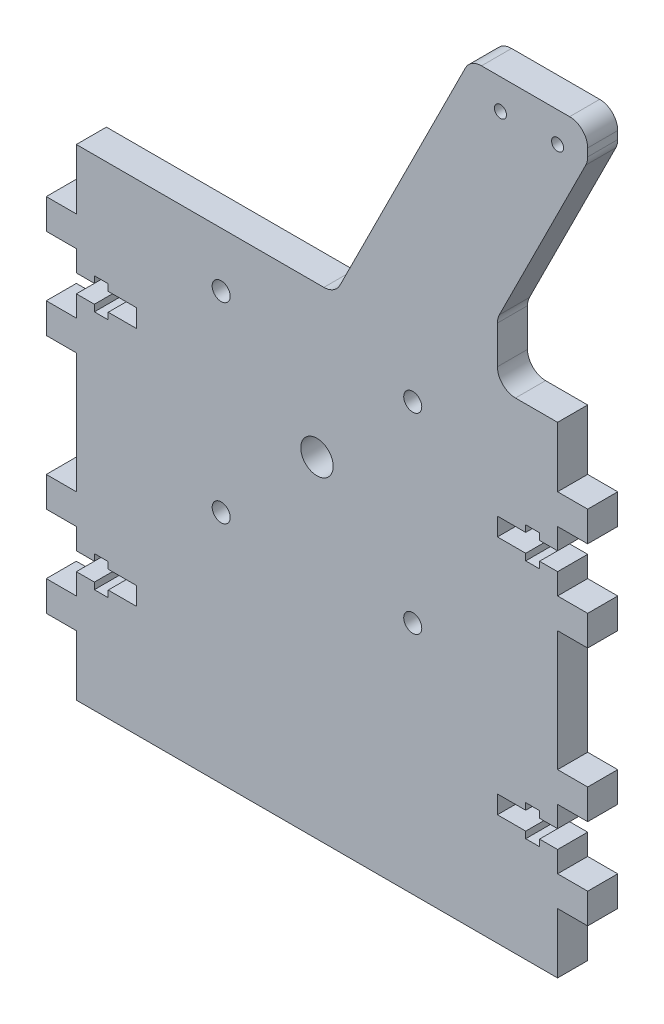
SolidWorks part; units mm, degrees
ref_plane "Front Plane" through (0, 0, 0) normal (0, 0, 1) x (1, 0, 0)
ref_plane "Top Plane" through (0, 0, 0) normal (0, 1, 0) x (1, 0, 0)
ref_plane "Right Plane" through (0, 0, 0) normal (1, 0, 0) x (0, 0, -1)
sketch "Sketch1" plane through (0, 0, 0) normal (0, 0, 1) x (1, 0, 0)
  line L0 (0, 0) -> (0, 80) construction
  line L1 (0, 80) -> (-80, 80)
  line L3 (-80, 0) -> (0, 0)
  line L4 (-40, 80) -> (-40, 0) construction
  line L5 (0, 40) -> (-80, 40) construction
  line L6 (0, 60) -> (-11.2208, 60) construction
  line L7 (0, 58.5) -> (0, 55)
  line L8 (5, 55) -> (5, 50)
  line L9 (5, 50) -> (0, 50)
  line L10 (5, 55) -> (0, 55)
  line L11 (0, 61.5) -> (0, 65)
  line L12 (0, 65) -> (5, 65)
  line L13 (5, 65) -> (5, 70)
  line L14 (5, 70) -> (0, 70)
  line L15 (0, 58.5) -> (0, 61.5) construction
  line L16 (0, 61.5) -> (-3, 61.5)
  line L17 (-5.3, 61.5) -> (-5.3, 62.6)
  line L18 (-3, 57.4) -> (-5.3, 57.4)
  line L19 (-3, 62.6) -> (-3, 61.5)
  line L20 (-5.3, 61.5) -> (-10, 61.5)
  line L21 (-10, 61.5) -> (-10, 58.5)
  line L22 (-10, 58.5) -> (-5.3, 58.5)
  line L23 (-3, 58.5) -> (-3, 57.4)
  line L24 (-5.3, 62.6) -> (-3, 62.6)
  line L25 (-5.3, 57.4) -> (-5.3, 58.5)
  line L26 (-3, 58.5) -> (0, 58.5)
  line L27 (-10, 60) -> (0, 60) construction
  line L28 (5, 10) -> (0, 10)
  line L29 (5, 15) -> (5, 10)
  line L30 (0, 15) -> (5, 15)
  line L31 (0, 18.5) -> (0, 15)
  line L32 (0, 18.5) -> (-3, 18.5)
  line L33 (-3, 17.4) -> (-3, 18.5)
  line L34 (-5.3, 17.4) -> (-3, 17.4)
  line L35 (-5.3, 18.5) -> (-5.3, 17.4)
  line L36 (-5.3, 18.5) -> (-10, 18.5)
  line L37 (-10, 18.5) -> (-10, 21.5)
  line L38 (-10, 21.5) -> (-5.3, 21.5)
  line L39 (-5.3, 22.6) -> (-5.3, 21.5)
  line L40 (-3, 22.6) -> (-5.3, 22.6)
  line L41 (-3, 21.5) -> (-3, 22.6)
  line L42 (-3, 21.5) -> (0, 21.5)
  line L43 (0, 21.5) -> (0, 25)
  line L44 (5, 25) -> (0, 25)
  line L45 (5, 25) -> (5, 30)
  line L46 (5, 30) -> (0, 30)
  line L47 (-85, 10) -> (-80, 10)
  line L48 (-85, 15) -> (-85, 10)
  line L49 (-80, 15) -> (-85, 15)
  line L50 (-80, 18.5) -> (-80, 15)
  line L51 (-80, 18.5) -> (-77, 18.5)
  line L52 (-77, 17.4) -> (-77, 18.5)
  line L53 (-74.7, 17.4) -> (-77, 17.4)
  line L54 (-74.7, 18.5) -> (-74.7, 17.4)
  line L55 (-74.7, 18.5) -> (-70, 18.5)
  line L56 (-70, 18.5) -> (-70, 21.5)
  line L57 (-70, 21.5) -> (-74.7, 21.5)
  line L58 (-74.7, 22.6) -> (-74.7, 21.5)
  line L59 (-77, 22.6) -> (-74.7, 22.6)
  line L60 (-77, 21.5) -> (-77, 22.6)
  line L61 (-77, 21.5) -> (-80, 21.5)
  line L62 (-80, 21.5) -> (-80, 25)
  line L63 (-85, 25) -> (-80, 25)
  line L64 (-85, 25) -> (-85, 30)
  line L65 (-85, 30) -> (-80, 30)
  line L66 (-85, 70) -> (-80, 70)
  line L67 (-85, 65) -> (-85, 70)
  line L68 (-80, 65) -> (-85, 65)
  line L69 (-80, 61.5) -> (-80, 65)
  line L70 (-80, 61.5) -> (-77, 61.5)
  line L71 (-77, 62.6) -> (-77, 61.5)
  line L72 (-74.7, 62.6) -> (-77, 62.6)
  line L73 (-74.7, 61.5) -> (-74.7, 62.6)
  line L74 (-74.7, 61.5) -> (-70, 61.5)
  line L75 (-70, 61.5) -> (-70, 58.5)
  line L76 (-70, 58.5) -> (-74.7, 58.5)
  line L77 (-74.7, 57.4) -> (-74.7, 58.5)
  line L78 (-77, 57.4) -> (-74.7, 57.4)
  line L79 (-77, 58.5) -> (-77, 57.4)
  line L80 (-77, 58.5) -> (-80, 58.5)
  line L81 (-80, 58.5) -> (-80, 55)
  line L82 (-85, 55) -> (-80, 55)
  line L83 (-85, 55) -> (-85, 50)
  line L84 (-85, 50) -> (-80, 50)
  line L85 (-80, 80) -> (-80, 70)
  line L86 (-80, 50) -> (-80, 30)
  line L87 (-80, 10) -> (-80, 0)
  line L88 (0, 0) -> (0, 10)
  line L89 (0, 30) -> (0, 50)
  line L90 (0, 70) -> (0, 80)
  circle B0 centre (-55.922, 70.922) radius 1.5
  circle B1 centre (-24.078, 70.922) radius 1.5
  circle B2 centre (-24.078, 39.078) radius 1.5
  circle B3 centre (-55.922, 39.078) radius 1.5
  circle B4 centre (-40, 55) radius 11.5
  dimension "D2" = 80
  dimension "D3" = 80
  dimension "D4" = 10
  dimension "D5" = 5
  dimension "D6" = 5
  dimension "D7" = 5.2
  dimension "D8" = 3
  dimension "D9" = 2.3
  dimension "D10" = 3
  dimension "D11" = 10
  dimension "D12" = 40
  dimension "D13" = 15
sketch_block_instance "Fixation Nema 17-1"
sketch_block "Fixation Nema 17"
extrude "Boss-Extrude1" add sketch "Sketch1" along normal blind 5
sketch "Sketch2" plane through (0, 0, 5) normal (0, 0, 1) x (1, 0, 0)
  circle A0 centre (-40, 55) radius 11.5
  circle A1 centre (-40, 55) radius 2.7
  circle A2 centre (-40, 55) radius 11.5 construction
  dimension "D1" = 5.4
extrude "Boss-Extrude2" add sketch "Sketch2" against normal up to vertex (5 mm away) up to point (5, 70, 0)
sketch "Sketch3" plane through (0, 0, 5) normal (0, 0, 1) x (1, 0, 0)
  line L1 (0, 80) -> (-80, 80) construction
  line L2 (5, 125) -> (-14.5, 125)
  line L4 (-37, 80) -> (-10, 80)
  line L5 (-9.5, 120) -> (0, 120) construction
  line L7 (-10, 80) -> (-10, 90)
  line L8 (-10, 90) -> (5, 120)
  line L9 (5, 120) -> (5, 125)
  line L10 (-14.5, 125) -> (-37, 80)
  line L11 (0, 70) -> (0, 80) construction
  line L12 (0, 30) -> (0, 50) construction
  circle A0 centre (-9.5, 120) radius 1
  circle A1 centre (0, 120) radius 1
  dimension "D1" = 9.5
  dimension "D3" = 2
  dimension "D2" = 5
  dimension "D4" = 40
  dimension "D5" = 5
  dimension "D6" = 5
  dimension "D7" = 5
  dimension "D9" = 10
  dimension "D10" = 10
  dimension "D11" = 30
extrude "Boss-Extrude3" add sketch "Sketch3" against normal up to vertex (5 mm away) up to point (-80, 80, 0)
fillet "Fillet1" radius 3 6 edges at (-10, 80, 2.5) (-10, 90, 2.5) (5, 120, 2.5) (5, 125, 2.5) (-14.5, 125, 2.5) (-37, 80, 2.5)
